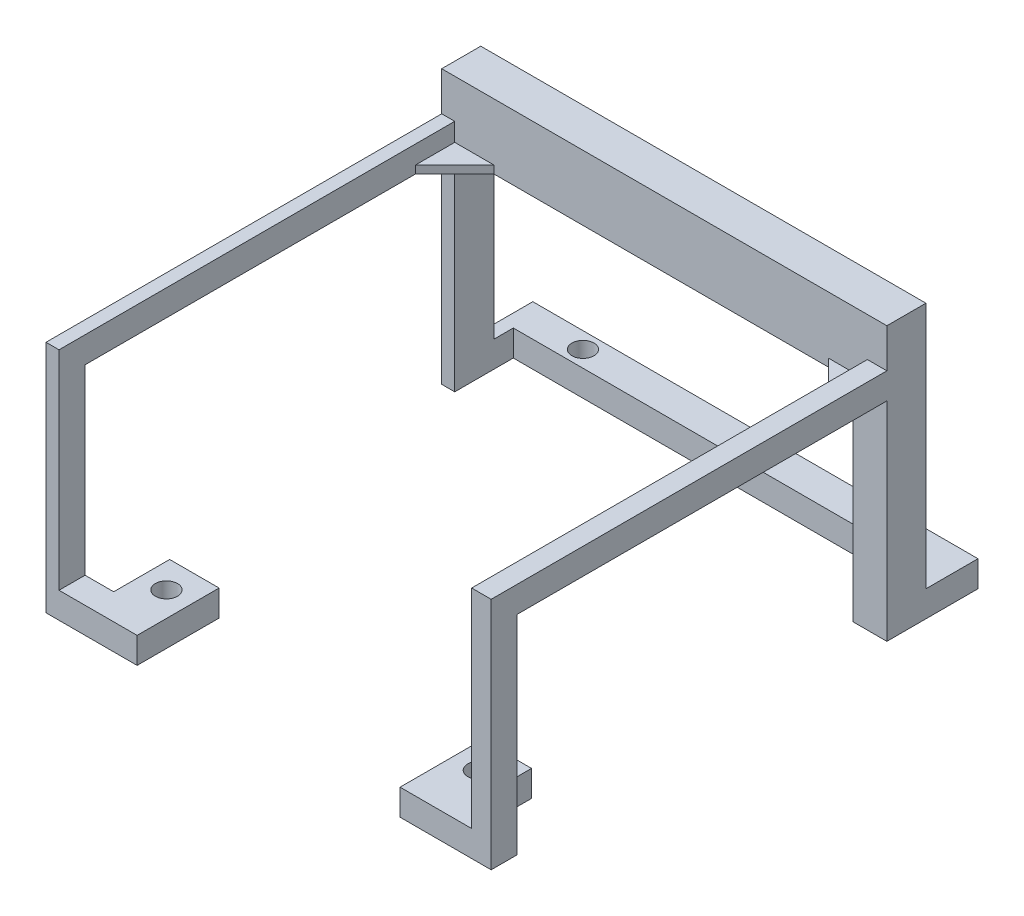
SolidWorks part; units mm, degrees
ref_plane "Front Plane" through (0, 0, 0) normal (0, 0, 1) x (1, 0, 0)
ref_plane "Top Plane" through (0, 0, 0) normal (0, 1, 0) x (1, 0, 0)
ref_plane "Right Plane" through (0, 0, 0) normal (1, 0, 0) x (0, 0, -1)
sketch "Sketch1" plane through (0, 0, 0) normal (0, 1, 0) x (1, 0, 0)
  line L0 (-55, 0) -> (55, 0) construction
  line L1 (-171, 12.5) -> (171, 12.5)
  line L3 (-158, 0) -> (158, 0)
  line L4 (171, 12.5) -> (171, 0)
  line L8 (-171, -12.5) -> (-158, -12.5)
  line L9 (-158, -12.5) -> (-158, 0)
  line L10 (0, -46.75) -> (0, 46.75) construction
  line L11 (171, -12.5) -> (158, -12.5)
  line L12 (158, -12.5) -> (158, 0)
  line L13 (171, 0) -> (171, -12.5)
  line L14 (-145.5, 6.25) -> (-145.5, 12.5) construction
  line L15 (-145.5, 6.25) -> (-145.5, 0) construction
  line L16 (-145.5, 0) -> (-158, 0) construction
  line L17 (-25.5, 6.25) -> (0, 6.25) construction
  line L18 (-145.5, 6.25) -> (-171, 6.25) construction
  line L19 (-171, 12.5) -> (-171, -12.5)
  circle A0 centre (-145.5, 6.25) radius 4.25
  circle A1 centre (145.5, 6.25) radius 4.25
  circle A2 centre (-25.5, 6.25) radius 4.25
  circle A3 centre (25.5, 6.25) radius 4.25
  point P6 (0, 0)
  dimension "D2" = 8.5
  dimension "D1" = 342
  dimension "D3" = 316
  dimension "D4" = 25
  dimension "D6" = 12.5
  dimension "D7" = 120
  dimension "D8" = 120
extrude "Boss-Extrude1" add sketch "Sketch1" along normal blind 10
sketch "Sketch2" plane through (0, 0, 12.5) normal (0, 0, 1) x (1, 0, 0)
  line L0 (-171, 0) -> (-171, 105)
  line L1 (-171, 10) -> (-171, 0) construction
  line L2 (-171, 105) -> (171, 105)
  line L3 (171, 105) -> (171, 0)
  line L4 (171, 10) -> (171, 0) construction
  line L5 (-171, 0) -> (-158, 0)
  line L6 (-158, 0) -> (-158, 80)
  line L7 (-158, 80) -> (158, 80)
  line L8 (158, 80) -> (158, 0)
  line L9 (-15.9953, 80) -> (-15.9953, 105) construction
  line L10 (-158, 52.4694) -> (-171, 52.4694) construction
  line L11 (55, 0) -> (-55, 0) construction
  line L12 (158, 0) -> (171, 0)
  line L16 (158, 0) -> (171, 0)
  line L17 (171, 0) -> (171, 10)
  line L18 (171, 10) -> (158, 10)
  line L19 (158, 10) -> (158, 0)
  line L21 (171, 0) -> (171, 10)
  line L23 (158, 10) -> (158, 0)
  dimension "D1" = 80
  dimension "D2" = 25
  dimension "D3" = 0
extrude "Boss-Extrude2" add sketch "Sketch2" against normal blind 5 and the other way blind 10
sketch "Sketch3" plane through (0, 0, 22.5) normal (0, 0, 1) x (1, 0, 0)
  line L0 (171, 105) -> (171, 0) construction
  line L1 (-171, 90) -> (171, 90)
  line L2 (-171, 90) -> (-171, 80)
  line L3 (-171, 80) -> (171, 80)
  line L4 (171, 90) -> (171, 80)
  line L5 (-158, 80) -> (158, 80) construction
  line L6 (-171, 0) -> (-171, 105) construction
  dimension "D1" = 10
extrude "Boss-Extrude3" add sketch "Sketch3" along normal blind 304
sketch "Sketch4" plane through (0, 105, 0) normal (0, 1, 0) x (1, 0, 0)
  line L2 (-171, -22.5) -> (171, -22.5) construction
  line L3 (-163.5, -22.5) -> (-5, -22.5)
  line L4 (-163.5, -22.5) -> (-163.5, -34.75)
  line L5 (-163.5, -326.5) -> (-5, -326.5)
  line L6 (163.5, -22.5) -> (163.5, -51.4723)
  line L8 (-163.5, -80.765) -> (-171, -80.765) construction
  line L9 (-171, -326.5) -> (-171, -22.5) construction
  line L10 (163.5, -70.9551) -> (171, -70.9551) construction
  line L11 (171, -326.5) -> (171, -22.5) construction
  line L12 (-5, -68.9608) -> (0, -68.9608) construction
  line L13 (171, -326.5) -> (-171, -326.5) construction
  line L14 (-163.5, -39.75) -> (-163.5, -326.5)
  line L19 (163.5, -51.4723) -> (163.5, -326.5)
  line L20 (5, -22.5) -> (163.5, -22.5)
  line L25 (43.2116, -39.75) -> (43.2116, -22.5) construction
  line L27 (-5, -22.5) -> (-5, -326.5)
  line L28 (5, -39.75) -> (5, -326.5)
  line L30 (5, -326.5) -> (163.5, -326.5)
  line L32 (5, -39.75) -> (5, -22.5)
  line L33 (-163.5, -34.75) -> (-163.5, -39.75)
  line L34 (171, -22.5) -> (-171, -22.5) construction
  line L35 (0, -46.75) -> (0, 46.75) construction
  line L36 (0, -68.9608) -> (5, -68.9608) construction
  dimension "D1" = 5
  dimension "D4" = 7.5
extrude "Cut-Extrude1" cut sketch "Sketch4" against normal up to next
ref_plane "Plane1" through (0, 0, 174.5) normal (0, 0, -1) x (-1, 0, 0)
mirror "Mirror3" about plane through (0, 0, 174.5) normal (0, 0, -1) of "Boss-Extrude2", "Boss-Extrude1"
mirror "Mirror4" about plane through (0, 0, 174.5) normal (0, 0, -1) of "Boss-Extrude1"
ref_plane "Plane2" through (0, 80, 0) normal (0, -1, 0) x (-1, 0, 0)
sketch "Sketch7" plane through (0, 80, 0) normal (0, -1, 0) x (-1, 0, 0)
  line L6 (-163.5, -22.5) -> (-148.5, -22.5)
  line L7 (-158, -22.5) -> (-171, -22.5) construction
  line L8 (-163.5, -22.5) -> (-163.5, -326.5) construction
  line L9 (-5, -22.5) -> (-158, -22.5) construction
  line L10 (-148.5, -22.5) -> (-163.5, -37.5)
  line L11 (-163.5, -37.5) -> (-163.5, -22.5)
  line L12 (-5, -22.5) -> (-20, -22.5)
  line L13 (-20, -22.5) -> (-5, -37.5)
  line L14 (-5, -326.5) -> (-5, -22.5) construction
  line L15 (-5, -37.5) -> (-5, -22.5)
  dimension "D1" = 15
extrude "Boss-Extrude4" add sketch "Sketch7" against normal blind 3
mirror "Mirror5" about plane through (0, 0, 174.5) normal (0, 0, -1) of "Boss-Extrude4" second plane through (0, 0, 0) second plane normal (1, 0, 0)
sketch "Sketch8" plane through (0, 0, 0) normal (1, 0, 0) x (0, 0, -1)
  line L0 (-326.5, 80) -> (-341.5, 80)
  line L1 (-22.5, 80) -> (-7.5, 80)
  line L2 (-349, 10) -> (-349, 0)
  line L3 (0, 10) -> (0, 0)
  line L16 (-361.5, 10) -> (-361.5, 0)
  line L17 (-361.5, 0) -> (-326.5, 0)
  line L18 (-326.5, 0) -> (-326.5, 80)
  line L19 (-326.5, 80) -> (-22.5, 80)
  line L20 (-22.5, 80) -> (-22.5, 0)
  line L21 (-22.5, 0) -> (12.5, 0)
  line L22 (12.5, 0) -> (12.5, 10)
  line L23 (12.5, 10) -> (-7.5, 10)
  line L24 (-7.5, 10) -> (-7.5, 105)
  line L25 (-7.5, 105) -> (-22.5, 105)
  line L26 (-22.5, 105) -> (-22.5, 90)
  line L27 (-22.5, 90) -> (-326.5, 90)
  line L28 (-326.5, 90) -> (-326.5, 105)
  line L29 (-326.5, 105) -> (-341.5, 105)
  line L30 (-341.5, 105) -> (-341.5, 10)
  line L31 (-341.5, 10) -> (-361.5, 10)
  line L33 (-349, 0) -> (-326.5, 0)
  line L34 (-326.5, 0) -> (-326.5, 80)
  line L36 (-22.5, 80) -> (-22.5, 0)
  line L37 (-22.5, 0) -> (0, 0)
  line L39 (0, 10) -> (-7.5, 10)
  line L40 (-7.5, 10) -> (-7.5, 80)
  line L46 (-341.5, 80) -> (-341.5, 10)
  line L47 (-341.5, 10) -> (-349, 10)
  dimension "D1" = 0
extrude "Boss-Extrude5" add sketch "Sketch8" along normal blind 5 and the other way blind 5
sketch "Sketch9" plane through (0, 0, 174.5) normal (0, 0, -1) x (-1, 0, 0)
  line L1 (-163.5, 10) -> (-136, 10)
  line L2 (-163.5, 80) -> (-163.5, 10)
  line L3 (-171, 80) -> (-171, 0)
  line L4 (-136, 10) -> (-136, 0)
  line L5 (-136, 0) -> (-171, 0)
  line L6 (-158, 0) -> (-171, 0) construction
  line L7 (-171, 80) -> (-163.5, 80)
  line L8 (-171, 10) -> (-171, 0) construction
  dimension "D1" = 35
extrude "Boss-Extrude6" add sketch "Sketch9" along normal blind 10
sketch "Sketch10" plane through (0, 10, 0) normal (0, 1, 0) x (1, 0, 0)
  line L0 (155, -164.5) -> (155, -143)
  line L1 (136, -164.5) -> (163.5, -164.5) construction
  line L2 (155, -143) -> (136, -143)
  line L3 (136, -143) -> (136, -164.5)
  line L4 (136, -164.5) -> (155, -164.5)
  line L5 (145.5, -153.75) -> (155, -153.75) construction
  line L6 (145.5, -153.75) -> (136, -153.75) construction
  line L7 (145.5, -153.75) -> (145.5, -143) construction
  line L8 (145.5, -153.75) -> (145.5, -164.5) construction
  circle A0 centre (145.5, -153.75) radius 4.25
  circle A1 centre (145.5, 6.25) radius 4.25 construction
  circle A2 centre (145.5, 6.25) radius 4.25 construction
  dimension "D1" = 160
extrude "Boss-Extrude7" add sketch "Sketch10" against normal blind 10
ref_plane "Plane3" through (85.5, 0, 0) normal (1, 0, 0) x (0, 0, -1)
mirror "Mirror6" about plane through (85.5, 0, 0) normal (1, 0, 0) of "Boss-Extrude6"
mirror "Mirror7" about plane through (85.5, 0, 0) normal (1, 0, 0) of "Boss-Extrude6", "Boss-Extrude7"
sketch "Sketch11" plane through (0, 0, 174.5) normal (0, 0, 1) x (1, 0, 0)
  line L0 (7.5, 80) -> (5, 80)
  line L1 (5, 80) -> (5, 10)
  line L2 (5, 10) -> (7.5, 10)
  line L3 (7.5, 10) -> (7.5, 80)
extrude "Cut-Extrude2" cut sketch "Sketch11" against normal up to next
mirror "Mirror8" about plane through (0, 0, 174.5) normal (0, 0, -1) of "Mirror7", "Mirror6", "Boss-Extrude6", "Boss-Extrude7"
mirror "Mirror9" about plane through (0, 0, 174.5) normal (0, 0, -1) of "Cut-Extrude2"
sketch "Sketch14" plane through (0, 0, 0) normal (1, 0, 0) x (0, 0, -1)
  line L1 (-433.126, 129.2099) -> (141.8228, 129.2099)
  line L2 (-433.126, 129.2099) -> (-433.126, -49.4047)
  line L3 (-433.126, -49.4047) -> (141.8228, -49.4047)
  line L4 (141.8228, 129.2099) -> (141.8228, -49.4047)
extrude "Cut-Extrude5" cut sketch "Sketch14" against normal up to next
sketch "Sketch15" plane through (0, 0, 174.5) normal (0, 0, -1) x (-1, 0, 0)
  line L1 (-218.083, 127.1937) -> (79.9101, 127.1937)
  line L2 (-218.083, 127.1937) -> (-218.083, -45.1397)
  line L3 (-218.083, -45.1397) -> (79.9101, -45.1397)
  line L4 (79.9101, 127.1937) -> (79.9101, -45.1397)
extrude "Cut-Extrude6" cut sketch "Sketch15" against normal up to next
